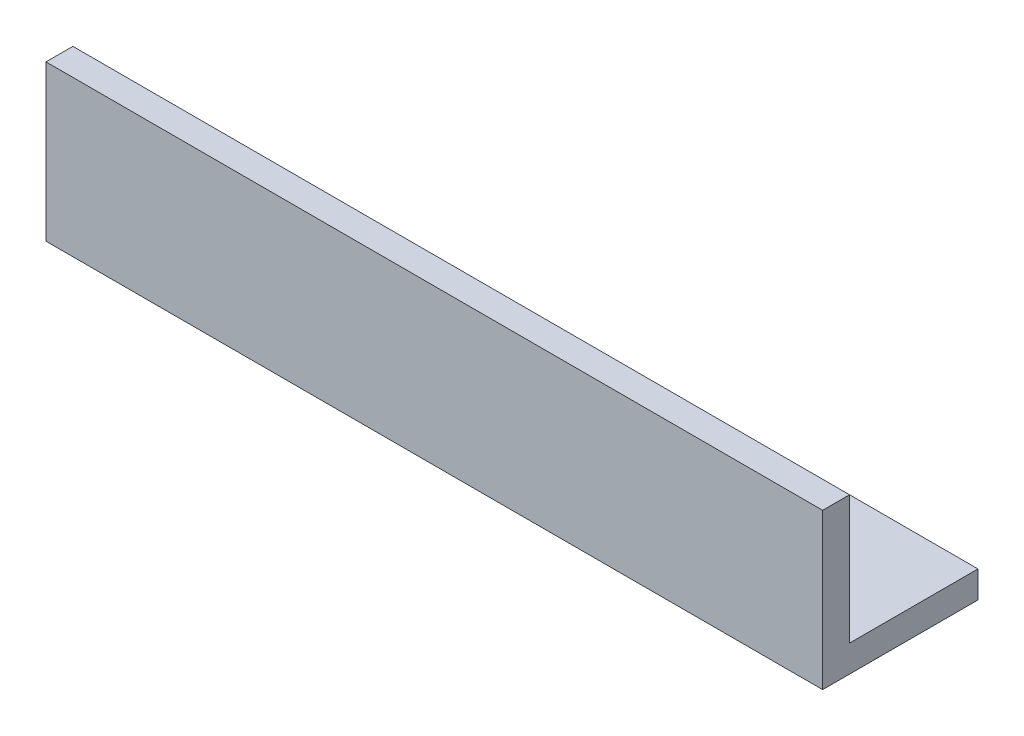
SolidWorks part; units mm, degrees
ref_plane "Front Plane" through (0, 0, 0) normal (0, 0, 1) x (1, 0, 0)
ref_plane "Top Plane" through (0, 0, 0) normal (0, 1, 0) x (1, 0, 0)
ref_plane "Right Plane" through (0, 0, 0) normal (1, 0, 0) x (0, 0, -1)
sketch "Sketch1" plane through (0, 0, 0) normal (1, 0, 0) x (0, 0, -1)
  line L0 (0, 0) -> (20, 0)
  line L1 (20, 0) -> (20, 3.4612)
  line L2 (20, 3.4612) -> (3.4612, 3.4612)
  line L3 (3.4612, 3.4612) -> (3.4612, 20)
  line L4 (3.4612, 20) -> (0, 20)
  line L5 (0, 20) -> (0, 0)
  dimension "D1" = 3.4612
  dimension "D2" = 20
extrude "Boss-Extrude1" add sketch "Sketch1" along normal blind 100
